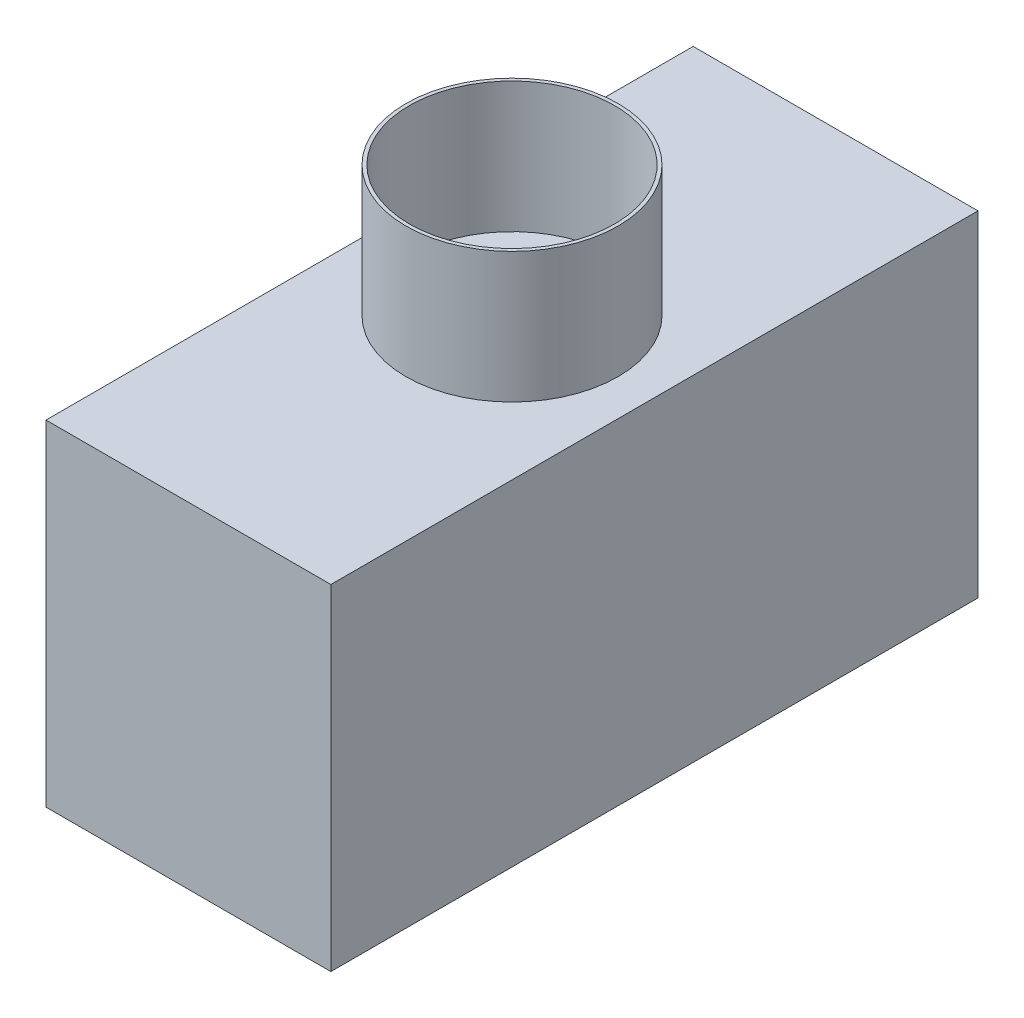
SolidWorks part; units mm, degrees
ref_plane "Front Plane" through (0, 0, 0) normal (0, 0, 1) x (1, 0, 0)
ref_plane "Top Plane" through (0, 0, 0) normal (0, 1, 0) x (1, 0, 0)
ref_plane "Right Plane" through (0, 0, 0) normal (1, 0, 0) x (0, 0, -1)
sketch "Sketch1" plane through (0, 0, 0) normal (0, 1, 0) x (1, 0, 0)
  line L1 (0, 0) -> (136.398, 0)
  line L2 (0, 0) -> (0, 309.88)
  line L3 (0, 309.88) -> (136.398, 309.88)
  line L4 (136.398, 0) -> (136.398, 309.88)
  dimension "D1" = 136.398
  dimension "D2" = 309.88
extrude "Extrude2" add sketch "Sketch1" along normal blind 160.528
ref_plane "Plane1" through (0, 160.528, 0) normal (0, 1, 0) x (-1, 0, 0)
sketch "Sketch3" plane through (0, 160.528, 0) normal (0, 1, 0) x (-1, 0, 0)
  line L0 (0, 0) -> (-136.398, 0) construction
  line L1 (0, -309.88) -> (0, 0) construction
  circle A0 centre (-68.199, -154.94) radius 50.8
  dimension "D1" = 101.6
  dimension "D2" = 154.94
  dimension "D3" = 68.199
extrude "Extrude3" add sketch "Sketch3" along normal blind 62.484
ref_plane "Plane2" through (0, 223.012, 0) normal (0, 1, 0) x (-1, 0, 0)
sketch "Sketch4" plane through (0, 223.012, 0) normal (0, 1, 0) x (-1, 0, 0)
  circle A0 centre (-68.199, -154.94) radius 76.2
sketch "Sketch5" plane through (0, 223.012, 0) normal (0, 1, 0) x (-1, 0, 0)
  circle A0 centre (-68.199, -154.94) radius 49.149
extrude "Cut-Extrude1" cut sketch "Sketch5" along normal blind 19.05 and the other way blind 62.484
sketch "Sketch6" plane through (0, 160.528, 0) normal (0, 1, 0) x (-1, 0, 0)
  line L0 (-68.199, -154.94) -> (-30.8231, -154.94)
